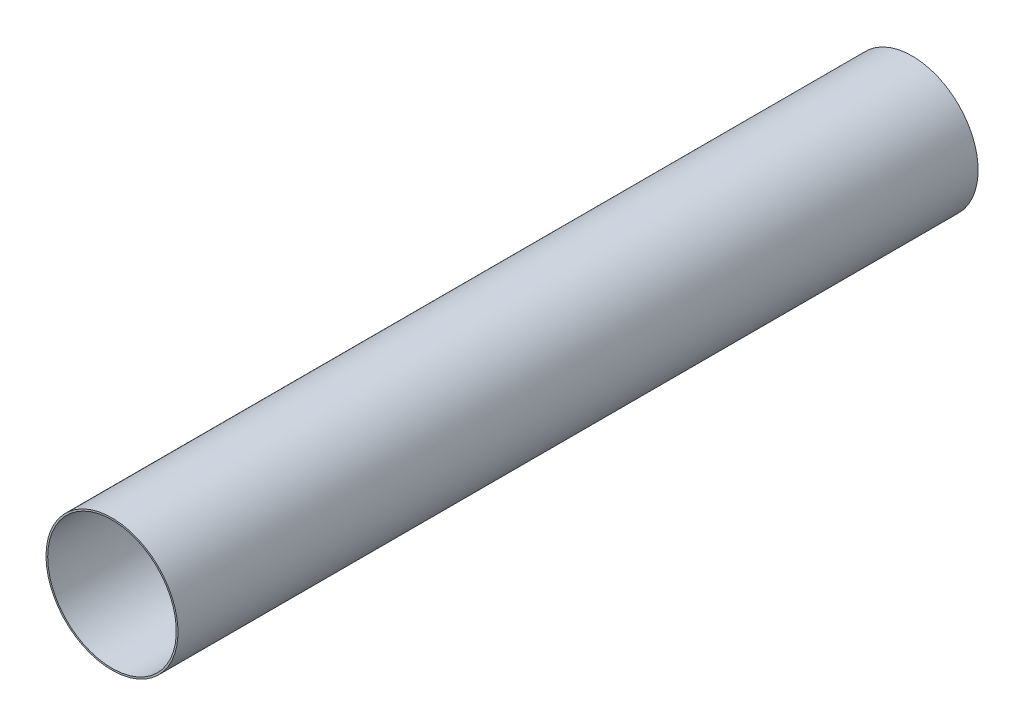
SolidWorks part; units mm, degrees
material "E-Glass Fiber"
ref_plane "Front" through (0, 0, 0) normal (0, 0, 1) x (1, 0, 0)
ref_plane "Top" through (0, 0, 0) normal (0, 1, 0) x (1, 0, 0)
ref_plane "Right" through (0, 0, 0) normal (1, 0, 0) x (0, 0, -1)
sketch "Sketch1" plane through (0, 0, 0) normal (0, 0, 1) x (1, 0, 0)
  circle A0 centre (0, 0) radius 78.35
  circle A1 centre (0, 0) radius 76.35
  dimension "D1" = 2
  dimension "D2" = 152.7
extrude "Boss-Extrude1" add sketch "Sketch1" along normal blind 950
